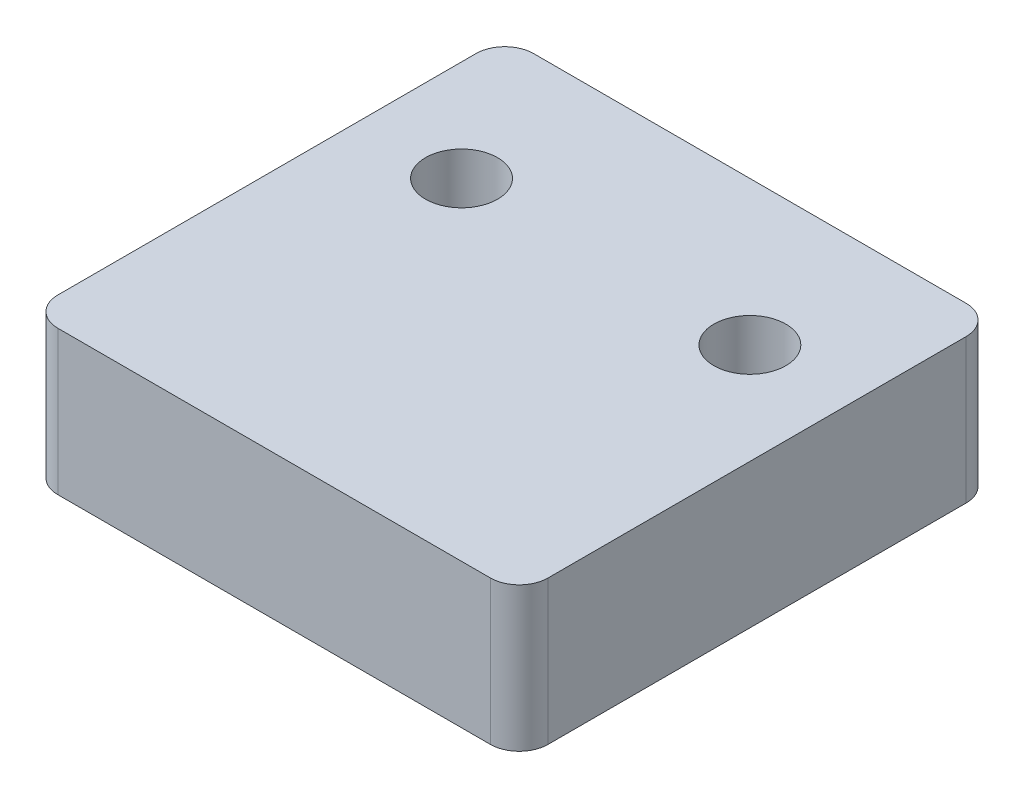
SolidWorks part; units mm, degrees
ref_plane "Front Plane" through (0, 0, 0) normal (0, 0, 1) x (1, 0, 0)
ref_plane "Top Plane" through (0, 0, 0) normal (0, 1, 0) x (1, 0, 0)
ref_plane "Right Plane" through (0, 0, 0) normal (1, 0, 0) x (0, 0, -1)
sketch "Sketch2" plane through (0, 0, 0) normal (0, 1, 0) x (1, 0, 0)
  line L1 (0, 0) -> (34, 0)
  line L2 (0, 0) -> (0, 33)
  line L3 (0, 33) -> (34, 33)
  line L4 (34, 0) -> (34, 33)
  dimension "D1" = 33
  dimension "D2" = 34
extrude "Boss-Extrude1" add sketch "Sketch2" along normal blind 10
fillet "Fillet1" radius 2 1 edges at (34, 5, 0)
fillet "Fillet2" radius 2 1 edges at (34, 5, -33)
fillet "Fillet3" radius 2 1 edges at (0, 5, -33)
fillet "Fillet4" radius 2 1 edges at (0, 5, 0)
sketch "Sketch3" plane through (0, 10, 0) normal (0, 1, 0) x (1, 0, 0)
  line L0 (32, 33) -> (2, 33) construction
  line L1 (0, 31) -> (0, 2) construction
  line L2 (34, 2) -> (34, 31) construction
  circle A0 centre (7, 23) radius 2.5
  circle A1 centre (27, 23) radius 2.5
  dimension "D3" = 5
  dimension "D4" = 5
  dimension "D1" = 10
  dimension "D2" = 7
  dimension "D5" = 7
extrude "Cut-Extrude1" cut sketch "Sketch3" against normal blind 10
